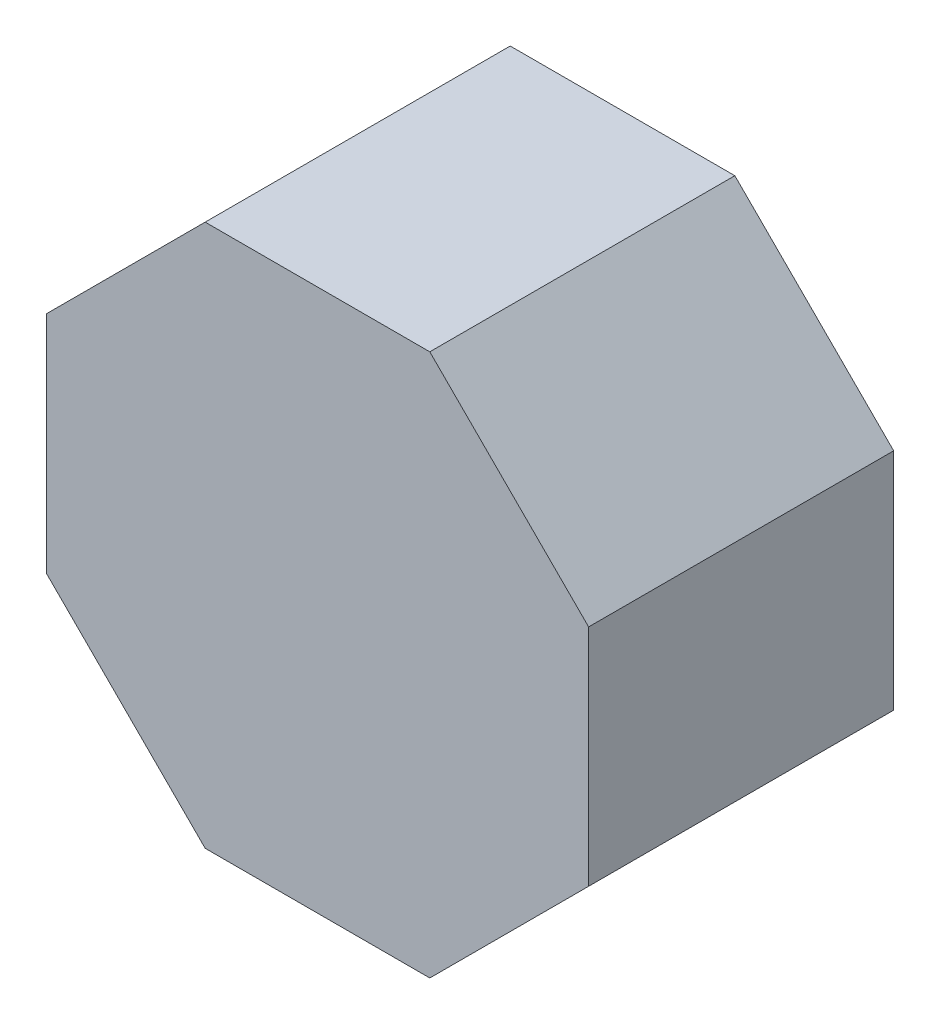
SolidWorks part; units mm, degrees
ref_plane "Спереди" through (0, 0, 0) normal (0, 0, 1) x (1, 0, 0)
ref_plane "Сверху" through (0, 0, 0) normal (0, 1, 0) x (1, 0, 0)
ref_plane "Справа" through (0, 0, 0) normal (1, 0, 0) x (0, 0, -1)
sketch "Эскиз1" plane through (0, 0, 0) normal (0, 0, 1) x (1, 0, 0)
  line L0 (-1.6569, 4) -> (1.6569, 4)
  line L1 (1.6569, 4) -> (4, 1.6569)
  line L2 (4, 1.6569) -> (4, -1.6569)
  line L3 (4, -1.6569) -> (1.6569, -4)
  line L4 (1.6569, -4) -> (-1.6569, -4)
  line L5 (-1.6569, -4) -> (-4, -1.6569)
  line L6 (-4, -1.6569) -> (-4, 1.6569)
  line L7 (-4, 1.6569) -> (-1.6569, 4)
  line L8 (-1.6569, 4) -> (1.6569, -4) construction
  point P8 (-4, 0)
  dimension "D1" = 8
extrude "Бобышка-Вытянуть1" add sketch "Эскиз1" along normal blind 4.5
